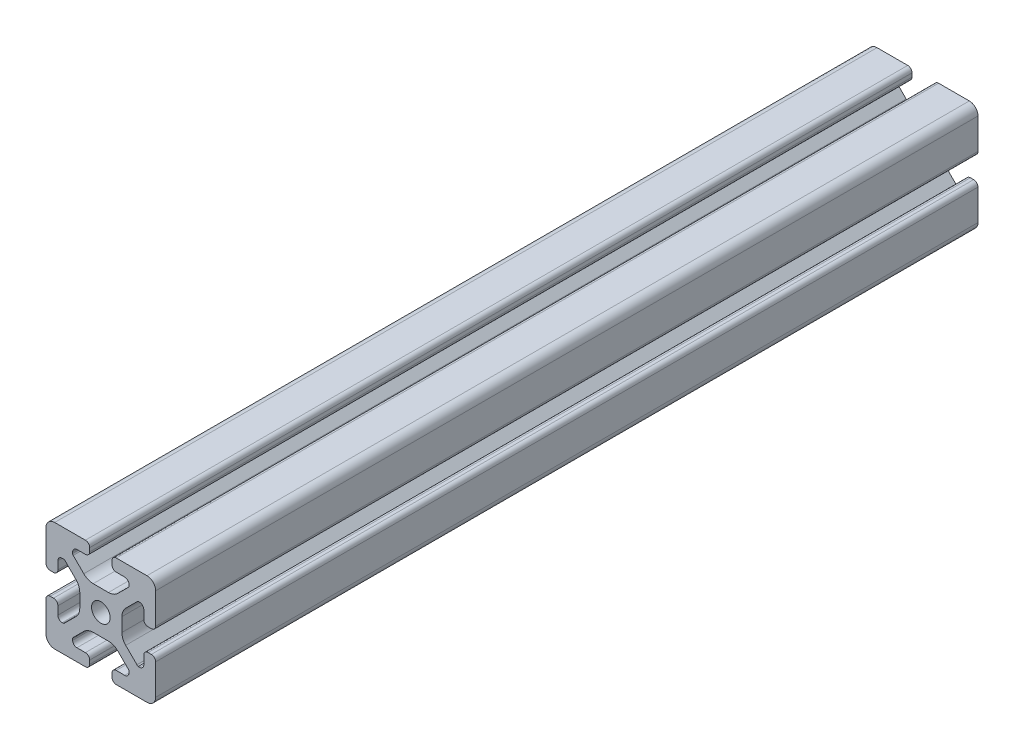
SolidWorks part; units mm, degrees
material "6105-T5 Aluminum"
ref_plane "Front Plane" through (0, 0, 0) normal (0, 0, 1) x (1, 0, 0)
ref_plane "Top Plane" through (0, 0, 0) normal (0, 1, 0) x (1, 0, 0)
ref_plane "Right Plane" through (0, 0, 0) normal (1, 0, 0) x (0, 0, -1)
sketch "Sketch1" plane through (0, 0, 0) normal (0, 0, 1) x (1, 0, 0)
  line L0 (0, 19.7407) -> (0, -19.7407) construction
  line L1 (19.0335, 0) -> (-20.7246, 0) construction
  line L2 (-8.715, -15.5246) -> (-5.63, -15.5246)
  line L3 (-10.285, -13.9546) -> (-10.285, -13.4925)
  line L4 (-6.2171, -9.1098) -> (-10.0624, -12.9551)
  line L5 (2.7773, -7.685) -> (-2.7773, -7.685)
  line L6 (10.0624, -12.9551) -> (6.2171, -9.1098)
  line L7 (10.285, -13.9546) -> (10.285, -13.4925)
  line L8 (5.63, -15.5246) -> (8.715, -15.5246)
  line L9 (4.06, -18.43) -> (4.06, -17.0946)
  line L10 (-4.06, -18.43) -> (-4.06, -17.0946)
  line L11 (15.68, -8.7154) -> (15.68, -5.63)
  line L12 (-14.11, -10.2854) -> (-13.8169, -10.2854)
  line L13 (20, -16.83) -> (20, -5.63)
  line L14 (20, 5.63) -> (20, 13.0011)
  line L15 (-16.83, 20) -> (-5.63, 20)
  line L16 (5.63, 20) -> (12.9796, 20)
  line L18 (-8.715, 15.5246) -> (-5.63, 15.5246)
  line L19 (-20, -17.0184) -> (-20, -5.7579)
  line L20 (-20, 5.573) -> (-20, 13.0045)
  line L21 (-15.68, -8.7154) -> (-15.68, -5.7579)
  line L23 (-16.6746, -20) -> (-5.63, -20)
  line L24 (5.63, -20) -> (13, -20)
  line L53 (14.11, -10.2854) -> (13.6201, -10.2854)
  line L54 (13.1637, -9.947) -> (9.0762, -5.8595)
  line L55 (7.685, -2.5008) -> (7.685, 2.5008)
  line L56 (9.0762, 5.8595) -> (13.2795, 10.0628)
  line L57 (13.8169, 10.2854) -> (14.11, 10.2854)
  line L58 (15.68, 8.7154) -> (15.68, 5.63)
  line L59 (17.25, 4.06) -> (18.43, 4.06)
  line L61 (20, 13.0011) -> (20, 16.83)
  line L62 (16.83, 20) -> (12.9796, 20)
  line L64 (4.06, 18.43) -> (4.06, 17.0946)
  line L65 (5.63, 15.5246) -> (8.715, 15.5246)
  line L66 (10.285, 13.9546) -> (10.285, 13.4925)
  line L67 (10.0624, 12.9551) -> (6.2171, 9.1098)
  line L68 (2.7773, 7.685) -> (-2.7773, 7.685)
  line L69 (-6.2171, 9.1098) -> (-10.0624, 12.9551)
  line L70 (-10.285, 13.4925) -> (-10.285, 13.9546)
  line L72 (-4.06, 17.0946) -> (-4.06, 18.43)
  line L75 (-20, 16.83) -> (-20, 13.0045)
  line L77 (-18.43, 4.003) -> (-17.25, 4.003)
  line L78 (-15.68, 5.573) -> (-15.68, 8.4757)
  line L79 (-14.0552, 10.0447) -> (-13.7199, 10.033)
  line L80 (-13.0405, 9.8238) -> (-9.0762, 5.8595)
  line L81 (-7.685, 2.5008) -> (-7.685, -2.5008)
  line L82 (-9.0762, -5.8595) -> (-13.2795, -10.0628)
  line L85 (-17.25, -4.1204) -> (-18.43, -4.1204)
  line L100 (13, -20) -> (16.83, -20)
  line L103 (18.43, -4.06) -> (17.25, -4.06)
  arc A0 (-5.63, -15.5246) -> (-4.06, -17.0946) centre (-5.63, -17.0946) cw
  arc A1 (-8.715, -15.5246) -> (-10.285, -13.9546) centre (-8.715, -13.9546) cw
  arc A2 (-10.285, -13.4925) -> (-10.0624, -12.9551) centre (-9.525, -13.4925) cw
  arc A3 (-6.2171, -9.1098) -> (-2.7773, -7.685) centre (-2.7773, -12.5496) cw
  arc A4 (2.7773, -7.685) -> (6.2171, -9.1098) centre (2.7773, -12.5496) cw
  arc A5 (10.0624, -12.9551) -> (10.285, -13.4925) centre (9.525, -13.4925) cw
  arc A6 (10.285, -13.9546) -> (8.715, -15.5246) centre (8.715, -13.9546) cw
  arc A7 (4.06, -17.0946) -> (5.63, -15.5246) centre (5.63, -17.0946) cw
  arc A8 (5.63, -20) -> (4.06, -18.43) centre (5.63, -18.43) cw
  arc A9 (-4.06, -18.43) -> (-5.63, -20) centre (-5.63, -18.43) cw
  circle A45 centre (0, 0) radius 3.4
  arc A46 (17.25, -4.06) -> (15.68, -5.63) centre (17.25, -5.63) ccw
  arc A47 (14.11, -10.2854) -> (15.68, -8.7154) centre (14.11, -8.7154) ccw
  arc A48 (13.1637, -9.947) -> (13.6201, -10.2854) centre (13.8117, -9.55) ccw
  arc A49 (7.685, -2.5008) -> (9.0762, -5.8595) centre (12.435, -2.5008) ccw
  arc A50 (9.0762, 5.8595) -> (7.685, 2.5008) centre (12.435, 2.5008) ccw
  arc A51 (13.8169, 10.2854) -> (13.2795, 10.0628) centre (13.8169, 9.5254) ccw
  arc A52 (15.68, 8.7154) -> (14.11, 10.2854) centre (14.11, 8.7154) ccw
  arc A53 (15.68, 5.63) -> (17.25, 4.06) centre (17.25, 5.63) ccw
  arc A54 (18.43, 4.06) -> (20, 5.63) centre (18.43, 5.63) ccw
  arc A55 (20, 16.83) -> (16.83, 20) centre (16.83, 16.83) ccw
  arc A56 (5.63, 20) -> (4.06, 18.43) centre (5.63, 18.43) ccw
  arc A57 (4.06, 17.0946) -> (5.63, 15.5246) centre (5.63, 17.0946) ccw
  arc A58 (10.285, 13.9546) -> (8.715, 15.5246) centre (8.715, 13.9546) ccw
  arc A59 (10.0624, 12.9551) -> (10.285, 13.4925) centre (9.525, 13.4925) ccw
  arc A60 (2.7773, 7.685) -> (6.2171, 9.1098) centre (2.7773, 12.5496) ccw
  arc A61 (-6.2171, 9.1098) -> (-2.7773, 7.685) centre (-2.7773, 12.5496) ccw
  arc A62 (-10.285, 13.4925) -> (-10.0624, 12.9551) centre (-9.525, 13.4925) ccw
  arc A63 (-8.715, 15.5246) -> (-10.285, 13.9546) centre (-8.715, 13.9546) ccw
  arc A64 (-5.63, 15.5246) -> (-4.06, 17.0946) centre (-5.63, 17.0946) ccw
  arc A65 (-4.06, 18.43) -> (-5.63, 20) centre (-5.63, 18.43) ccw
  arc A66 (-16.83, 20) -> (-20, 16.83) centre (-16.83, 16.83) ccw
  arc A67 (-20, 5.573) -> (-18.43, 4.003) centre (-18.43, 5.573) ccw
  arc A68 (-17.25, 4.003) -> (-15.68, 5.573) centre (-17.25, 5.573) ccw
  arc A69 (-14.0552, 10.0447) -> (-15.68, 8.4757) centre (-14.11, 8.4757) ccw
  arc A70 (-13.0405, 9.8238) -> (-13.7199, 10.033) centre (-13.5779, 9.2864) ccw
  arc A71 (-7.685, 2.5008) -> (-9.0762, 5.8595) centre (-12.435, 2.5008) ccw
  arc A72 (-9.0762, -5.8595) -> (-7.685, -2.5008) centre (-12.435, -2.5008) ccw
  arc A73 (-13.8169, -10.2854) -> (-13.2795, -10.0628) centre (-13.8169, -9.5254) ccw
  arc A74 (-15.68, -8.7154) -> (-14.11, -10.2854) centre (-14.11, -8.7154) ccw
  arc A75 (-15.68, -5.7579) -> (-17.25, -4.1204) centre (-17.2485, -5.6904) ccw
  arc A76 (-18.43, -4.1204) -> (-20, -5.7579) centre (-18.4315, -5.6904) ccw
  arc A77 (-20, -17.0184) -> (-16.6746, -20) centre (-16.8354, -16.8341) ccw
  arc A88 (16.83, -20) -> (20, -16.83) centre (16.83, -16.83) ccw
  arc A89 (20, -5.63) -> (18.43, -4.06) centre (18.43, -5.63) ccw
  dimension "D2" = 6.8
  dimension "D7" = 20.57
  dimension "D1" = 40
  dimension "D3" = 4.32
  dimension "D4" = 15.37
  dimension "D5" = 20
  dimension "D6" = 4.32
  dimension "D9" = 15.37
extrude "Extrude1" add sketch "Sketch1" against normal blind 300
